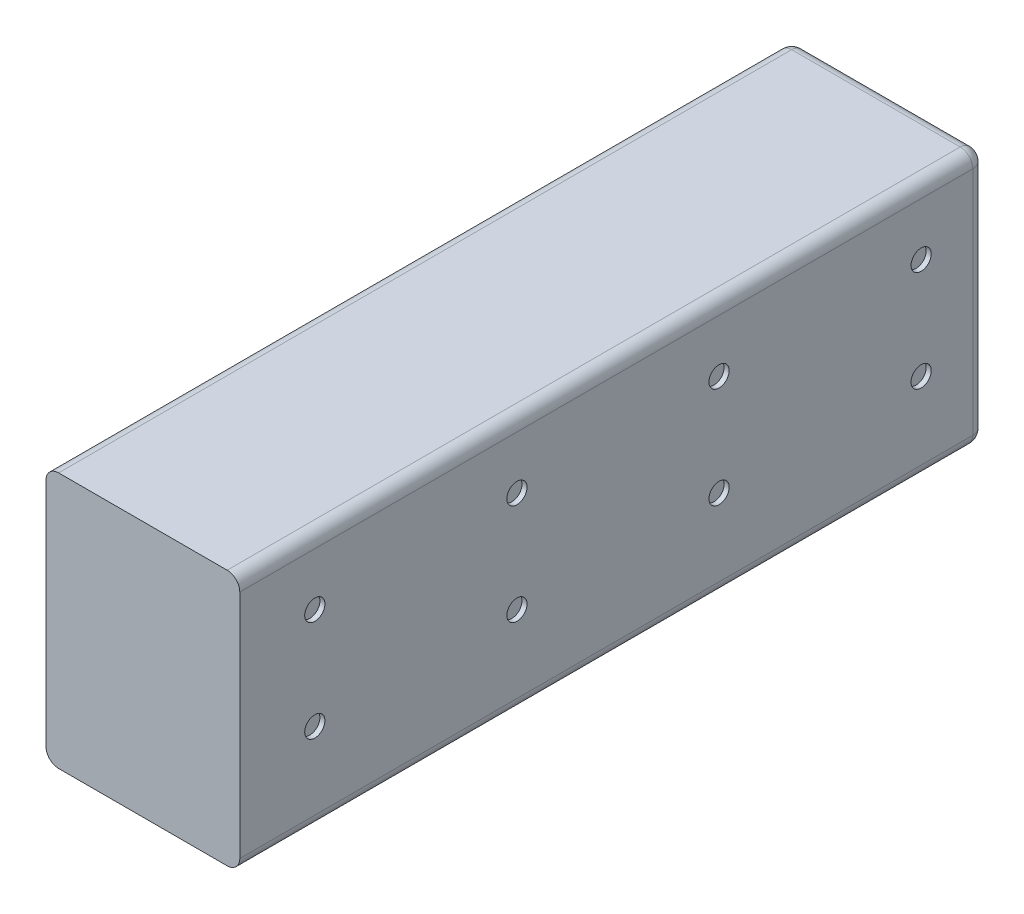
SolidWorks part; units mm, degrees
material "ABS"
ref_plane "Front Plane" through (0, 0, 0) normal (0, 0, 1) x (1, 0, 0)
ref_plane "Top Plane" through (0, 0, 0) normal (0, 1, 0) x (1, 0, 0)
ref_plane "Right Plane" through (0, 0, 0) normal (1, 0, 0) x (0, 0, -1)
sketch "Sketch2" plane through (0, 0, 0) normal (0, 0, 1) x (1, 0, 0)
  line L1 (0, 0) -> (76.708, 0)
  line L2 (0, 0) -> (0, 101.346)
  line L3 (0, 101.346) -> (76.708, 101.346)
  line L4 (76.708, 0) -> (76.708, 101.346)
extrude "Boss-Extrude1" add sketch "Sketch2" along normal blind 295.148
sketch "Sketch3" plane through (76.708, 0, 0) normal (1, 0, 0) x (0, 0, -1)
  circle A0 centre (-265.4456, 75.4508) radius 4
  circle A1 centre (-185.4456, 75.4508) radius 4
  circle A2 centre (-105.4456, 75.4508) radius 4
  circle A3 centre (-25.4456, 75.4508) radius 4
  circle A4 centre (-185.4456, 35.4508) radius 4
  circle A5 centre (-105.4456, 35.4508) radius 4
  circle A6 centre (-25.4456, 35.4508) radius 4
  circle A7 centre (-265.4456, 35.4508) radius 4
  dimension "D1" = 4
  dimension "D2" = 2
extrude "Cut-Extrude1" cut sketch "Sketch3" against normal blind 2
ref_plane "Plane1" through (38.354, 0, 0) normal (-1, 0, 0) x (0, 0, 1)
mirror "Mirror1" about plane through (38.354, 0, 0) normal (-1, 0, 0) of "Cut-Extrude1"
fillet "Fillet1" radius 5 4 edges at (0, 0, 147.574) (76.708, 0, 147.574) (76.708, 101.346, 147.574) (0, 101.346, 147.574)
fillet "Fillet2" radius 5 8 edges at (75.2435, 99.8815, 0) (75.2435, 1.4645, 0) (1.4645, 1.4645, 0) (1.4645, 99.8815, 0) (38.354, 0, 0) (76.708, 50.673, 0) (0, 50.673, 0) (38.354, 101.346, 0)
